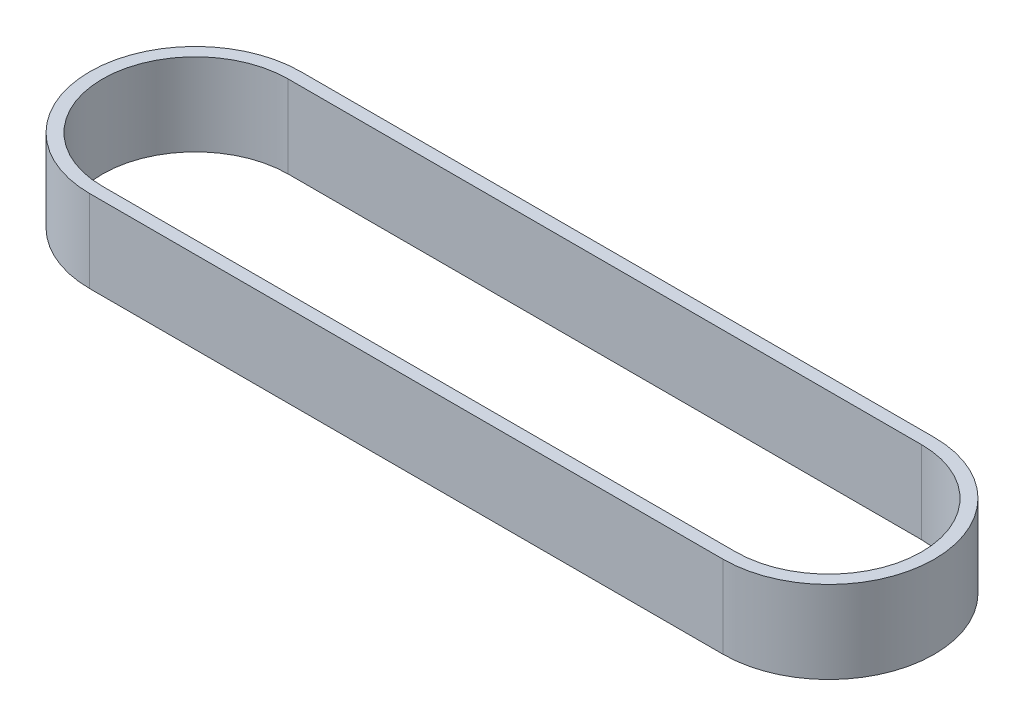
SolidWorks part; units mm, degrees
material "Silicon Rubber"
ref_plane "Front Plane" through (0, 0, 0) normal (0, 0, 1) x (1, 0, 0)
ref_plane "Top Plane" through (0, 0, 0) normal (0, 1, 0) x (1, 0, 0)
ref_plane "Right Plane" through (0, 0, 0) normal (1, 0, 0) x (0, 0, -1)
sketch "Sketch1" plane through (0, 0, 0) normal (0, 1, 0) x (1, 0, 0)
  line L0 (-150, 0) -> (150, 0) construction
  line L1 (-150, 44) -> (150, 44)
  line L2 (-150, -44) -> (150, -44)
  line L3 (-150, 50) -> (150, 50)
  line L4 (-150, -50) -> (150, -50)
  arc A0 (-150, 44) -> (-150, -44) centre (-150, 0) ccw
  arc A1 (150, -44) -> (150, 44) centre (150, 0) ccw
  arc A2 (150, -50) -> (150, 50) centre (150, 0) ccw
  arc A3 (-150, 50) -> (-150, -50) centre (-150, 0) ccw
  point P3 (0, 0)
  point P8 (0, 44)
  dimension "D2" = 44
  dimension "D1" = 300
  dimension "D4" = 300
  dimension "D3" = 6
extrude "Boss-Extrude1" add sketch "Sketch1" along normal blind 39
